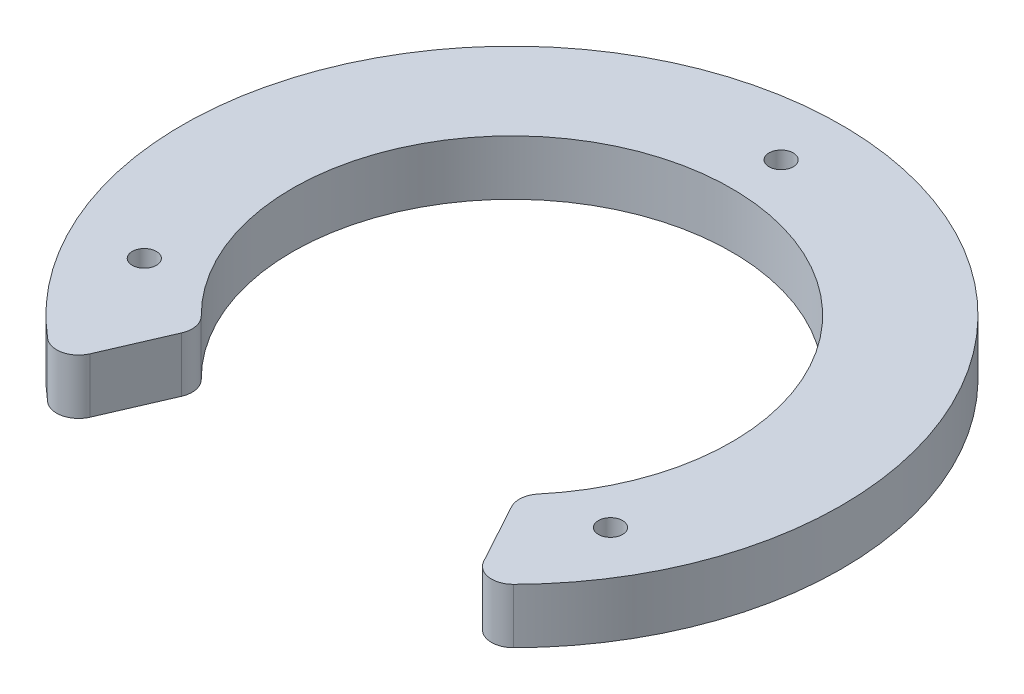
SolidWorks part; units mm, degrees
material "Thornel Mat VMA"
ref_plane "前视基准面" through (0, 0, 0) normal (0, 0, 1) x (1, 0, 0)
ref_plane "上视基准面" through (0, 0, 0) normal (0, 1, 0) x (1, 0, 0)
ref_plane "右视基准面" through (0, 0, 0) normal (1, 0, 0) x (0, 0, -1)
other "Configuration Table"
sketch "草图1" plane through (0, 0, 0) normal (0, 1, 0) x (1, 0, 0)
  circle A0 centre (0, 0) radius 20
  circle A1 centre (0, 0) radius 24.5 construction
  circle A2 centre (0, 0) radius 30
  circle A3 centre (0, 24.5) radius 1.1
  circle A4 centre (21.2176, -12.25) radius 1.1
  circle A5 centre (-21.2176, -12.25) radius 1.1
  point P13 (0, 0)
  dimension "D1" = 40
  dimension "D2" = 49
  dimension "D3" = 60
  dimension "D4" = 2.2
extrude "凸台-拉伸1" add sketch "草图1" along normal blind 5
sketch "草图2" plane through (0, 5, 0) normal (0, 1, 0) x (1, 0, 0)
  line L1 (19.3391, -22.9346) -> (14.4011, -13.8783)
  line L2 (-13.0832, -15.1271) -> (-17.1796, -24.5939)
  circle A0 centre (0, 0) radius 20 construction
  circle A1 centre (0, 0) radius 30 construction
  arc A2 (-13.0832, -15.1271) -> (14.4011, -13.8783) centre (0, 0) ccw
  arc A3 (-17.1796, -24.5939) -> (19.3391, -22.9346) centre (0, 0) ccw
extrude "切除-拉伸1" cut sketch "草图2" against normal blind 10
fillet "圆角1" radius 2 4 edges at (14.4011, 2.5, 13.8783) (19.3391, 2.5, 22.9346) (-13.0832, 2.5, 15.1271) (-17.1796, 2.5, 24.5939)
